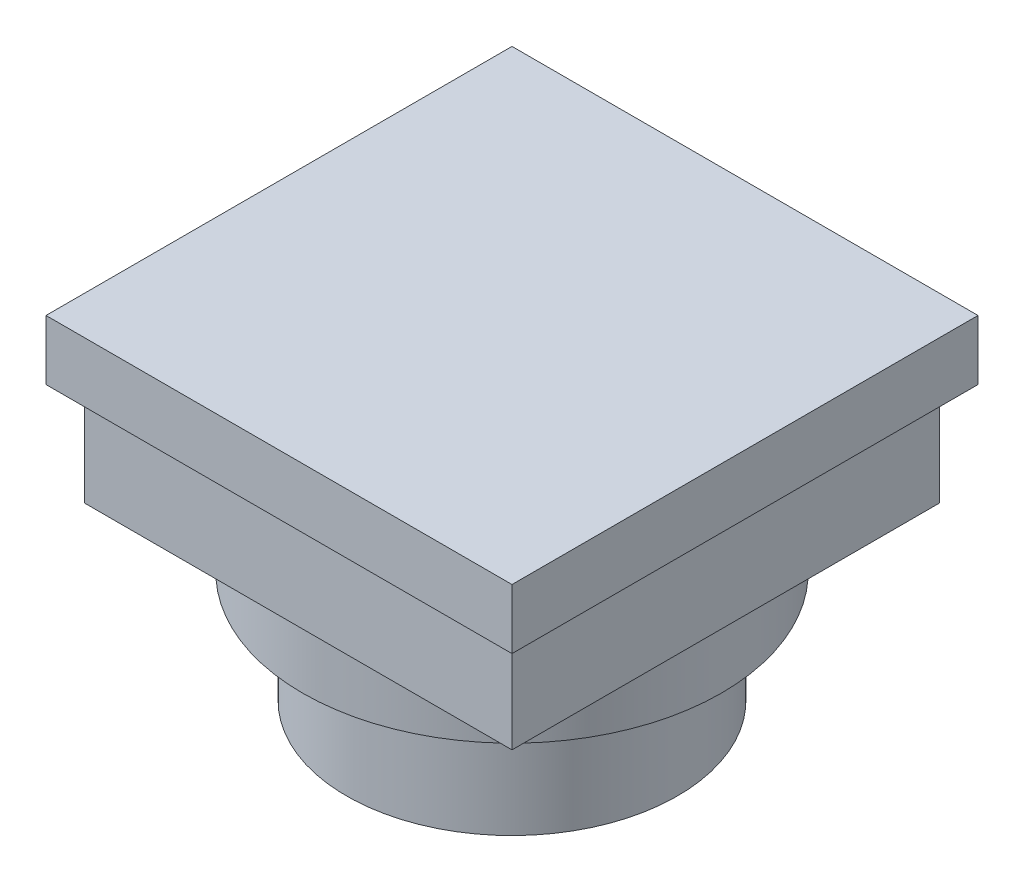
SolidWorks part; units mm, degrees
ref_plane "Front Plane" through (0, 0, 0) normal (0, 0, 1) x (1, 0, 0)
ref_plane "Top Plane" through (0, 0, 0) normal (0, 1, 0) x (1, 0, 0)
ref_plane "Right Plane" through (0, 0, 0) normal (1, 0, 0) x (0, 0, -1)
sketch "Sketch1" plane through (0, 0, 0) normal (0, 1, 0) x (1, 0, 0)
  line L1 (-2.725, -2.725) -> (2.725, -2.725)
  line L2 (-2.725, -2.725) -> (-2.725, 2.725)
  line L3 (-2.725, 2.725) -> (2.725, 2.725)
  line L4 (2.725, -2.725) -> (2.725, 2.725)
  line L5 (-2.725, -2.725) -> (2.725, 2.725) construction
  line L6 (-2.725, 2.725) -> (2.725, -2.725) construction
  point P0 (0, 0)
  dimension "D1" = 5.45
extrude "Boss-Extrude1" add sketch "Sketch1" along normal blind 0.7
sketch "Sketch2" plane through (0, 0, 0) normal (0, -1, 0) x (1, 0, 0)
  line L1 (-2.5, -2.5) -> (2.5, -2.5)
  line L2 (-2.5, -2.5) -> (-2.5, 2.5)
  line L3 (-2.5, 2.5) -> (2.5, 2.5)
  line L4 (2.5, -2.5) -> (2.5, 2.5)
  line L5 (-2.5, -2.5) -> (2.5, 2.5) construction
  line L6 (-2.5, 2.5) -> (2.5, -2.5) construction
  point P0 (0, 0)
  dimension "D1" = 5
extrude "Boss-Extrude2" add sketch "Sketch2" along normal blind 1.2
sketch "Sketch4" plane through (0, -1.2, 0) normal (0, -1, 0) x (1, 0, 0)
  circle A0 centre (0, 0) radius 2.45
  dimension "D1" = 4.9
extrude "Boss-Extrude3" add sketch "Sketch4" along normal blind 0.7
sketch "Sketch5" plane through (0, -1.9, 0) normal (0, -1, 0) x (1, 0, 0)
  circle A0 centre (0, 0) radius 1.935
  circle A1 centre (0, 0) radius 0.35
  dimension "D1" = 3.87
  dimension "D2" = 0.7
extrude "Boss-Extrude4" add sketch "Sketch5" along normal blind 1.3
